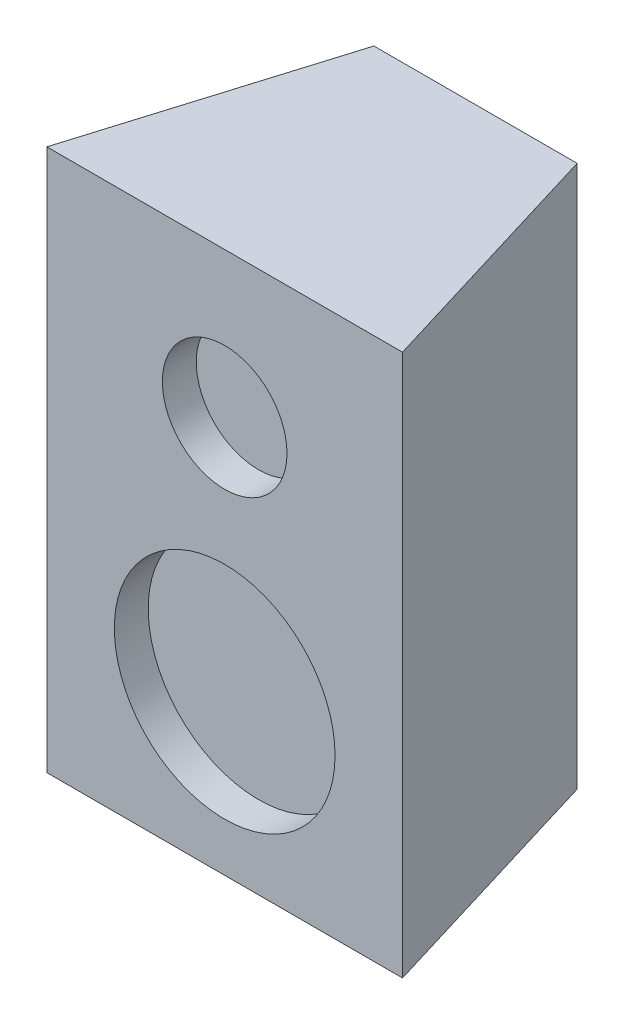
SolidWorks part; units mm, degrees
ref_plane "Front Plane" through (0, 0, 0) normal (0, 0, 1) x (1, 0, 0)
ref_plane "Top Plane" through (0, 0, 0) normal (0, 1, 0) x (1, 0, 0)
ref_plane "Right Plane" through (0, 0, 0) normal (1, 0, 0) x (0, 0, -1)
sketch "Sketch1" plane through (0, 0, 0) normal (0, 1, 0) x (1, 0, 0)
  line L0 (-76.5116, 0) -> (56.8384, 0)
  line L1 (56.8384, 0) -> (28.2634, 94.0534)
  line L2 (28.2634, 94.0534) -> (-47.9366, 94.0534)
  line L3 (-47.9366, 94.0534) -> (-76.5116, 0)
  dimension "D1" = 76.2
  dimension "D2" = 133.35
extrude "Boss-Extrude1" add sketch "Sketch1" along normal blind 203.2
sketch "Sketch2" plane through (0, 0, 0) normal (0, 0, 1) x (1, 0, 0)
  line L0 (-9.8366, 203.2) -> (-9.8366, 0) construction
  line L1 (-76.5116, 203.2) -> (56.8384, 203.2) construction
  line L2 (-76.5116, 0) -> (56.8384, 0) construction
  circle A0 centre (-9.8366, 148.6912) radius 23.3653
  circle A1 centre (-9.8366, 59.6018) radius 41.3785
  point P10 (-9.8366, 59.6018)
extrude "Cut-Extrude1" cut sketch "Sketch2" against normal blind 12.7
